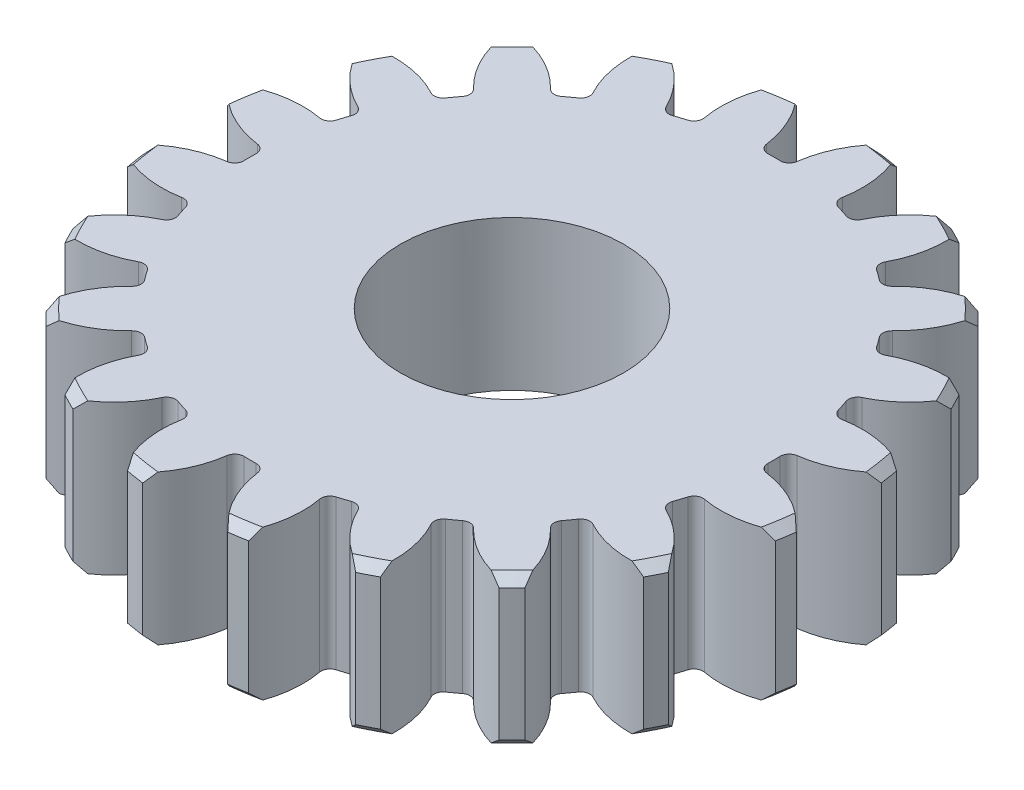
SolidWorks part; units mm, degrees
ref_plane "Front Plane" through (0, 0, 0) normal (0, 0, 1) x (1, 0, 0)
ref_plane "Top Plane" through (0, 0, 0) normal (0, 1, 0) x (1, 0, 0)
ref_plane "Right Plane" through (0, 0, 0) normal (1, 0, 0) x (0, 0, -1)
sketch "Sketch1" plane through (0, 0, 0) normal (0, 1, 0) x (1, 0, 0)
  circle A0 centre (0, 0) radius 20
  circle A1 centre (0, 0) radius 22
  circle A2 centre (0, 0) radius 17.5
  dimension "D1" = 40
  dimension "addendum" = 2
  dimension "dedendum" = 2.5
extrude "Boss-Extrude1" add sketch "Sketch1" along normal blind 10 contours A1
sketch "Sketch2" plane through (0, 0, 0) normal (0, -1, 0) x (1, 0, 0)
  line L0 (0, 0) -> (0, 41.9432) construction
  line L1 (-0.9626, 17.4735) -> (0, 0) construction
  line L2 (0.9626, 17.4735) -> (0, 0) construction
  line L3 (-1.5692, 19.9383) -> (1.5692, 19.9383) construction
  line L4 (-5.0152, 27.5) -> (-4.0305, 25.3393) construction
  line L5 (-1.5692, 19.9383) -> (4.5196, 22.7132) construction
  line L6 (-1.5692, 19.9383) -> (1.8919, 20.2107) construction
  line L7 (0, 0) -> (6.5686, 41.4726) construction
  line L8 (1.5692, 19.9383) -> (4.6689, 19.4474) construction
  arc A0 (-2.8367, 21.8164) -> (-0.9626, 17.4735) centre (-7.8048, 17.0966) cw
  circle A1 centre (0, 0) radius 22 construction
  circle A2 centre (0, 0) radius 17.5 construction
  arc A3 (2.8367, 21.8164) -> (0.9626, 17.4735) centre (7.8048, 17.0966) ccw
  circle A4 centre (0, 0) radius 20 construction
  arc A5 (0.9626, 17.4735) -> (-0.9626, 17.4735) centre (0, 0) ccw
  arc A6 (2.8367, 21.8164) -> (-2.8367, 21.8164) centre (0, 0) ccw
  point P13 (-1.5692, 19.9383)
  point P14 (1.5692, 19.9383)
  dimension "D1" = 20
  dimension "D2" = 9
extrude "Cut-Extrude1" cut sketch "Sketch2" against normal up to surface (10 mm away) up to face at (0, 10, 22)
fillet "Fillet1" radius 0.6 2 edges at (0.9626, 5, 17.4735) (-0.9626, 5, 17.4735)
chamfer "Chamfer1" distance 0.6 angle 45 2 edges at (0, 0, -22) (0, 10, -22)
pattern_circular "CirPattern1" count 20 over 360 about axis through (0, 0, 0) along (0, 1, 0) of "Cut-Extrude1", "Fillet1"
sketch "Sketch3" plane through (0, 0, 0) normal (0, -1, 0) x (1, 0, 0)
  circle A0 centre (0, 0) radius 7.45
  dimension "D1" = 14.9
extrude "Cut-Extrude2" cut sketch "Sketch3" against normal up to surface (10 mm away) up to face at (0, 10, 0)
sketch "Sketch4" plane through (0, 10, 0) normal (0, 1, 0) x (1, 0, 0)
  point P0 (0, 0)
equation "\"module\"= 2mm"
equation "\"noTeeth\"= 20"
equation "\"pressureAngle\"= 20deg"
equation "\"width\"= 10mm"
equation "\"D1@Sketch1\"=\"module\"*\"noTeeth\""
equation "\"dedendum@Sketch1\" = \"module\" * 1.25"
equation "\"addendum@Sketch1\" = \"module\""
equation "\"D1@Sketch2\"=\"pressureAngle\""
equation "\"D2@Sketch2\"=180/\"noTeeth\""
equation "\"D1@Fillet1\"=0.3*\"module\""
equation "\"D1@Chamfer1\"=0.3*\"module\""
equation "\"D1@CirPattern1\"=\"noTeeth\""
